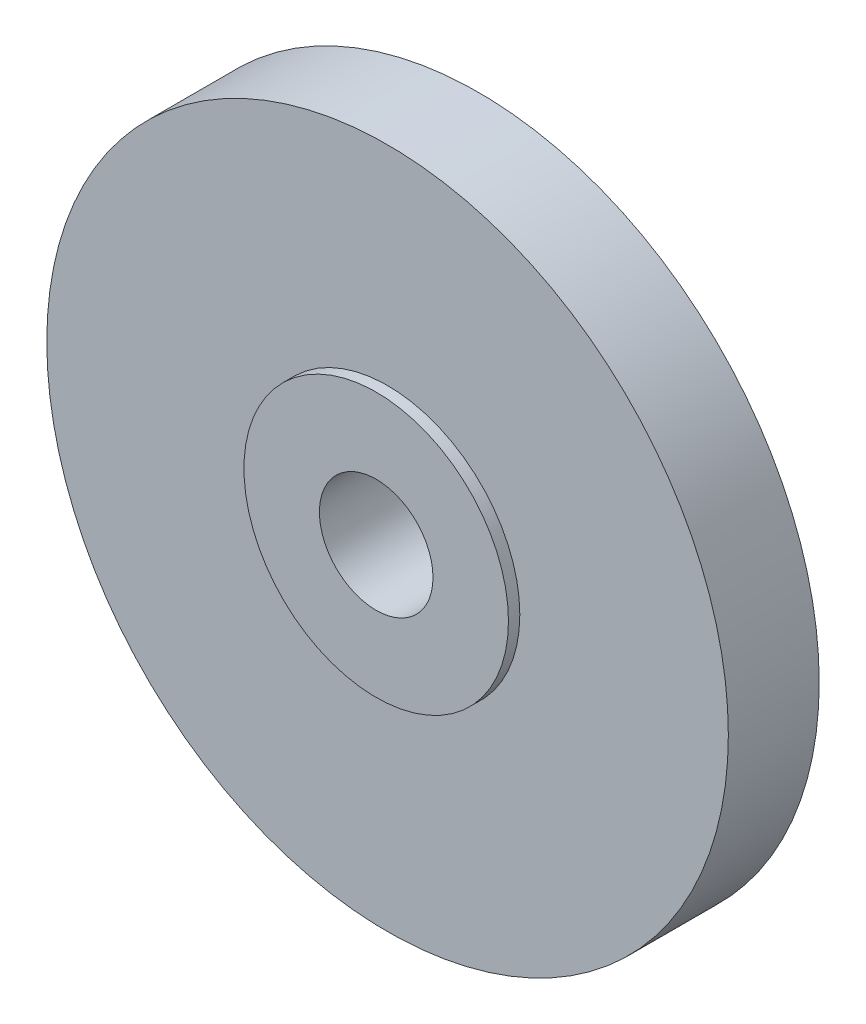
SolidWorks part; units mm, degrees
ref_plane "Alzado" through (0, 0, 0) normal (0, 0, 1) x (1, 0, 0)
ref_plane "Planta" through (0, 0, 0) normal (0, 1, 0) x (1, 0, 0)
ref_plane "Vista lateral" through (0, 0, 0) normal (1, 0, 0) x (0, 0, -1)
sketch "Croquis1" plane through (0, 0, 0) normal (0, 0, 1) x (1, 0, 0)
  circle A0 centre (-32.2118, 9.0923) radius 300
extrude "Saliente-Extruir1" add sketch "Croquis1" along normal blind 80
sketch "Croquis2" plane through (0, 0, 80) normal (0, 0, 1) x (1, 0, 0)
  circle A1 centre (-32.2118, 9.0923) radius 116.43
extrude "Saliente-Extruir2" add sketch "Croquis2" along normal blind 10
sketch "Croquis3" plane through (0, 0, 90) normal (0, 0, 1) x (1, 0, 0)
  circle A1 centre (-32.2118, 9.0923) radius 50
extrude "Cortar-Extruir2" cut sketch "Croquis3" against normal blind 90
